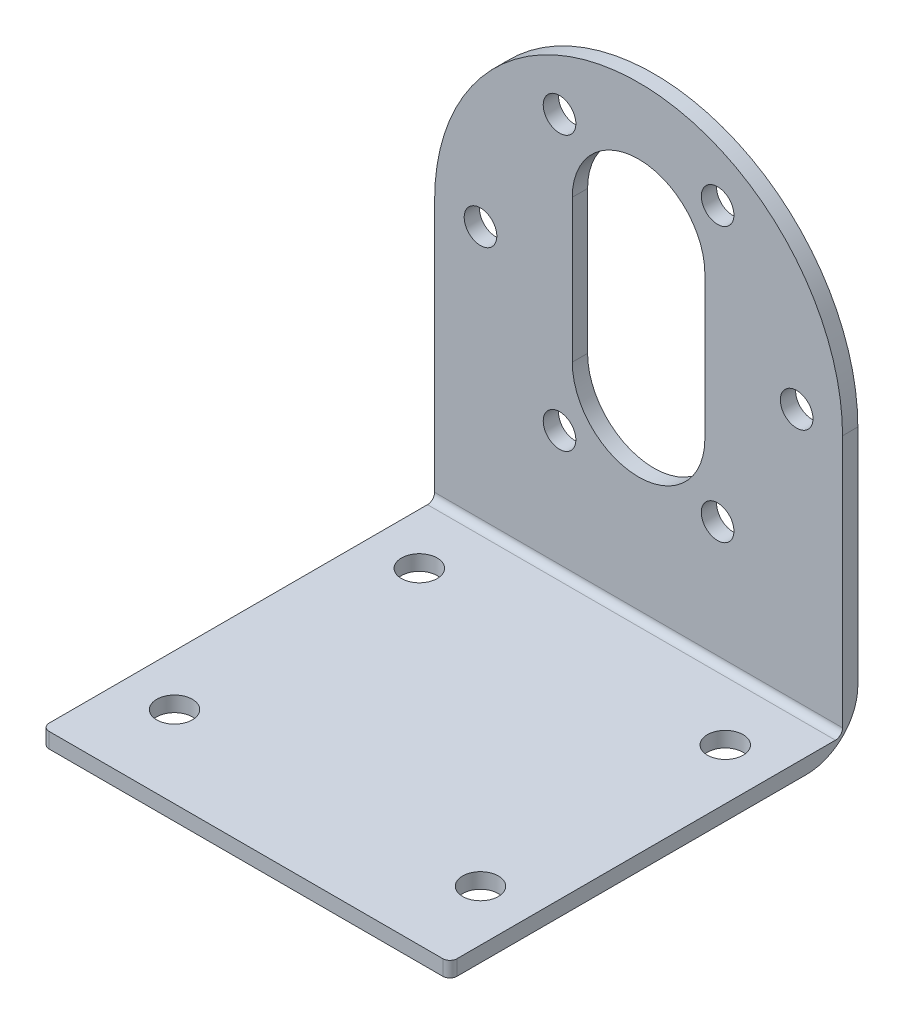
SolidWorks part; units mm, degrees
ref_plane "Front Plane" through (0, 0, 0) normal (0, 0, 1) x (1, 0, 0)
ref_plane "Top Plane" through (0, 0, 0) normal (0, 1, 0) x (1, 0, 0)
ref_plane "Right Plane" through (0, 0, 0) normal (1, 0, 0) x (0, 0, -1)
sketch "Sketch1" plane through (0, 0, 0) normal (1, 0, 0) x (0, 0, -1)
  line L0 (0, 1.5) -> (0, 0)
  line L1 (0, 0) -> (34.9633, 0)
  line L2 (40, 5.0367) -> (40, 47)
  line L3 (40, 47) -> (38.5, 47)
  line L4 (38.5, 47) -> (38.5, 1.5)
  line L5 (38.5, 1.5) -> (0, 1.5)
  arc A0 (34.9633, 0) -> (40, 5.0367) centre (34.9633, 5.0367) ccw
  dimension "D1" = 1.5
  dimension "D2" = 47
  dimension "D3" = 40
extrude "MainPiece" add sketch "Sketch1" along normal blind 40
sketch "Sketch2" plane through (0, 0, 0) normal (0, -1, 0) x (-1, 0, 0)
  line L6 (-5, 8) -> (-5, 32) construction
  line L7 (-5, 32) -> (-35, 32) construction
  line L8 (-35, 32) -> (-35, 8) construction
  line L9 (-35, 8) -> (-5, 8) construction
  line L11 (-40, 0) -> (0, 0) construction
  line L12 (0, 0) -> (0, 34.9633) construction
  circle A1 centre (-5, 8) radius 1.75
  circle A2 centre (-35, 8) radius 1.75
  circle A3 centre (-35, 32) radius 1.75
  circle A4 centre (-5, 32) radius 1.75
  dimension "D1" = 3.5
  dimension "D2" = 8
  dimension "D3" = 5
  dimension "D4" = 30
  dimension "D5" = 24
extrude "ChassisHoles" cut sketch "Sketch2" against normal up to next
sketch "Sketch3" plane through (0, 0, -40) normal (0, 0, -1) x (-1, 0, 0)
  line L1 (-40, 47) -> (0, 47) construction
  line L2 (-40, 5.0367) -> (-40, 47) construction
  line L3 (-40, 27) -> (-40, 47)
  line L4 (-40, 47) -> (0, 47)
  line L5 (0, 47) -> (0, 27)
  line L6 (0, 5.0367) -> (0, 47) construction
  arc A0 (0, 27) -> (-40, 27) centre (-20, 27) ccw
  point P3 (-20, 47)
  line M3 (0, 5.0367) -> (0, 47)
  line M4 (0, 47) -> (-40, 47)
  line M5 (-40, 47) -> (-40, 5.0367)
extrude "Dome" cut sketch "Sketch3" against normal up to next contours A0 L4 M5 | A0 M3 M4
sketch "Sketch4" plane through (0, 0, -40) normal (0, 0, -1) x (-1, 0, 0)
  line L0 (-26.5, 20) -> (-26.5, 34)
  line L1 (-20, 34) -> (-20, 47) construction
  line L2 (-13.5, 34) -> (-13.5, 20)
  line L3 (-20, 27) -> (-35.5002, 27) construction
  line L4 (-20, 34) -> (-20, 20) construction
  arc A3 (0, 27) -> (-40, 27) centre (-20, 27) ccw construction
  circle A4 centre (-35.5002, 27) radius 1.6
  arc A5 (-26.5, 34) -> (-13.5, 34) centre (-20, 34) cw
  arc A6 (-13.5, 20) -> (-26.5, 20) centre (-20, 20) cw
  circle A7 centre (-27.7501, 40.4235) radius 1.6
  circle A8 centre (-12.2499, 40.4235) radius 1.6
  circle A9 centre (-4.4998, 27) radius 1.6
  circle A10 centre (-12.2499, 13.5765) radius 1.6
  circle A11 centre (-27.7501, 13.5765) radius 1.6
  point P14 (-20, 47)
  dimension "D3" = 14
  dimension "D4" = 3.2
  dimension "D2" = 6.5
  dimension "D1" = 13
  dimension "D6" = 15.5002
  dimension "D7" = 20
  dimension "D5" = 6
extrude "WheelMotorGuide" cut sketch "Sketch4" against normal up to next
fillet "Fillet1" radius 0.7 3 edges at (0, 0.75, 0) (40, 0.75, 0) (20, 1.5, -38.5)
